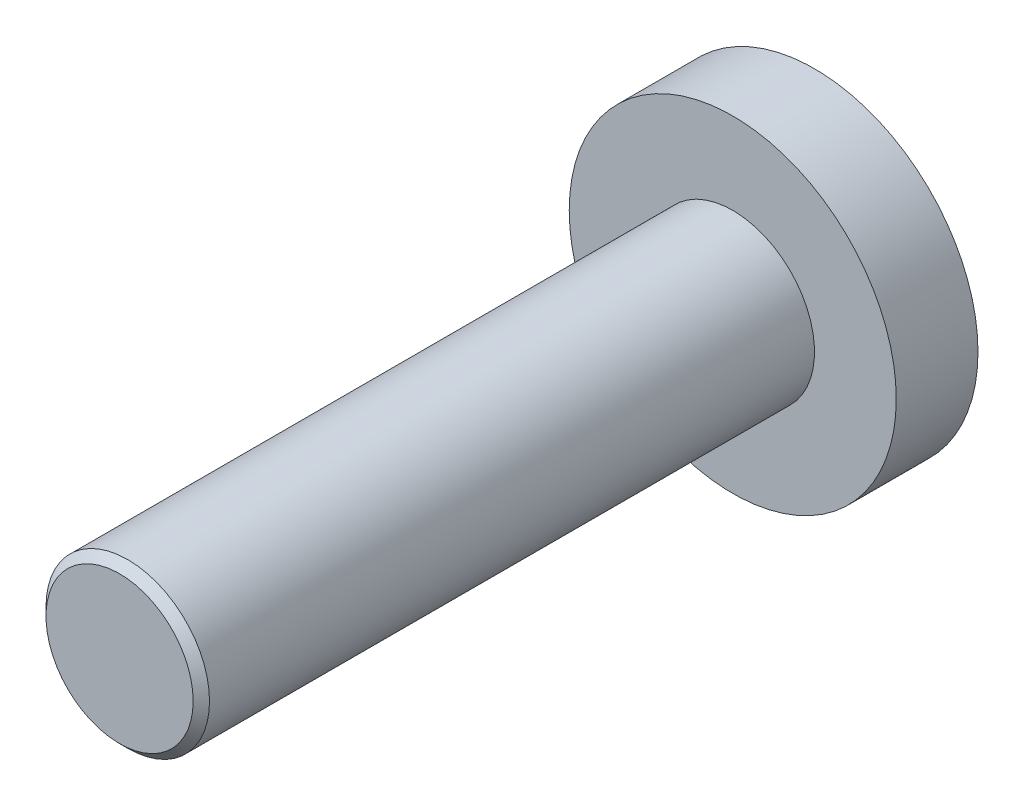
SolidWorks part; units mm, degrees
material "AISI 1020"
ref_plane "前视基准面" through (0, 0, 0) normal (0, 0, 1) x (1, 0, 0)
ref_plane "上视基准面" through (0, 0, 0) normal (0, 1, 0) x (1, 0, 0)
ref_plane "右视基准面" through (0, 0, 0) normal (1, 0, 0) x (0, 0, -1)
sketch "草图1" plane through (0, 0, 0) normal (0, 0, 1) x (1, 0, 0)
  circle A0 centre (0, 0) radius 2
  dimension "D1" = 4
extrude "拉伸1" add sketch "草图1" along normal blind 15
sketch "草图2" plane through (0, 0, 0) normal (0, 0, -1) x (-1, 0, 0)
  circle A0 centre (0, 0) radius 4
  dimension "D1" = 8
extrude "拉伸2" add sketch "草图2" along normal blind 2
chamfer "倒角1" distance 0.2 angle 45 1 edges at (2, 0, 15)
